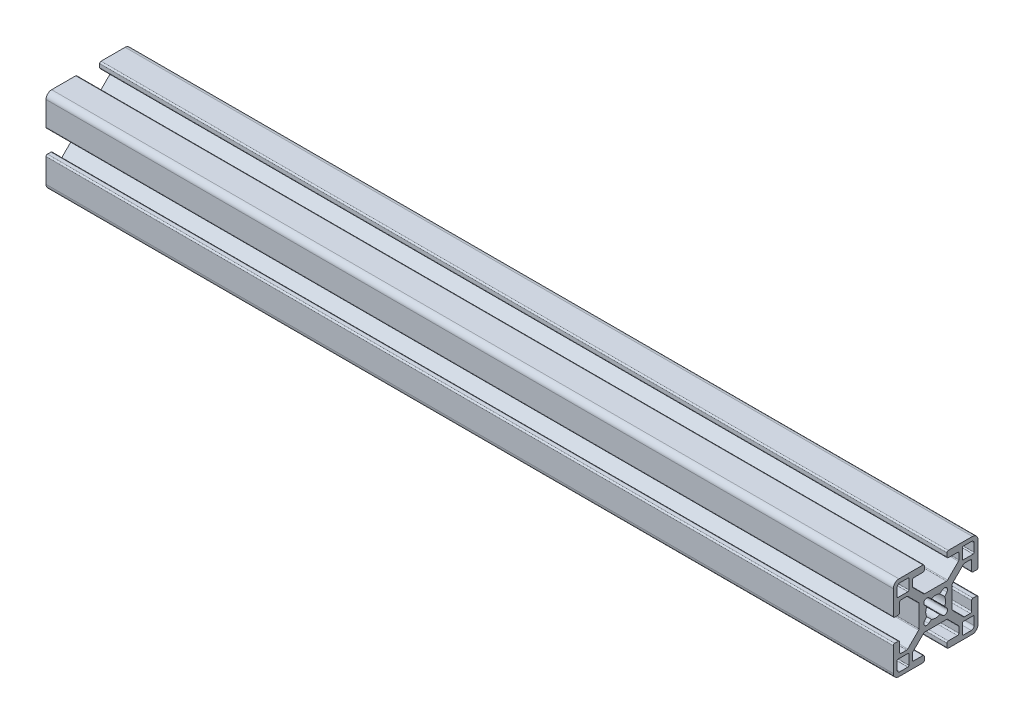
SolidWorks part; units mm, degrees
ref_plane "Front" through (0, 0, 0) normal (0, 0, 1) x (1, 0, 0)
ref_plane "Top" through (0, 0, 0) normal (0, 1, 0) x (1, 0, 0)
ref_plane "Right" through (0, 0, 0) normal (1, 0, 0) x (0, 0, -1)
sketch "Esboço1" plane through (0, 0, 0) normal (0, 1, 0) x (1, 0, 0)
  line L0 (0, 0) -> (300, 0)
  dimension "D1" = 300
other "Perfil com. aluminio PERFIL COMER. 30 X 30(1)"
ref_plane "Plano1" through (0, 0, 0) normal (1, 0, 0) x (0, 0, -1)
sketch "Esboço11" plane through (0, 0, 0) normal (1, 0, 0) x (0, 0, -1)
  line L10 (-3.1849, 1.488) -> (-3.9634, 2.4631)
  line L11 (-2.4631, 3.9634) -> (-1.488, 3.1849)
  line L16 (-9.46, 13.26) -> (-9.46, 9.84)
  line L17 (-9.84, 9.46) -> (-13.26, 9.46)
  line L18 (-13.64, 9.84) -> (-13.64, 12.64)
  line L19 (-12.64, 13.64) -> (-9.84, 13.64)
  line L44 (0, 5.8727) -> (-3.8729, 5.8727)
  line L45 (-4.2264, 6.0192) -> (-8.0736, 9.8663)
  line L46 (-8.22, 10.2198) -> (-8.22, 12.25)
  line L47 (-7.72, 12.75) -> (-4.5, 12.75)
  line L48 (-4, 13.25) -> (-4, 14.5)
  line L49 (-4.5, 15) -> (-13, 15)
  line L50 (-15, 13) -> (-15, 4.5)
  line L51 (-14.5, 4) -> (-13.25, 4)
  line L52 (-12.75, 4.5) -> (-12.75, 7.72)
  line L53 (-12.25, 8.22) -> (-10.2198, 8.22)
  line L54 (-9.8663, 8.0736) -> (-6.0192, 4.2264)
  line L55 (-5.8727, 3.8729) -> (-5.8727, 0)
  line L84 (13.64, 12.64) -> (13.64, 9.84)
  line L91 (15, 4.5) -> (15, 13)
  line L92 (13, 15) -> (4.5, 15)
  line L93 (4, 14.5) -> (4, 13.25)
  line L94 (4.5, 12.75) -> (7.72, 12.75)
  line L95 (8.22, 12.25) -> (8.22, 10.2198)
  line L96 (8.0736, 9.8663) -> (4.2264, 6.0192)
  line L97 (3.8729, 5.8727) -> (0, 5.8727)
  line L98 (1.488, 3.1849) -> (2.4631, 3.9634)
  line L99 (3.9634, 2.4631) -> (3.1849, 1.488)
  line L100 (5.8727, 0) -> (5.8727, 3.8729)
  line L101 (6.0192, 4.2264) -> (9.8663, 8.0736)
  line L102 (10.2198, 8.22) -> (12.25, 8.22)
  line L103 (12.75, 7.72) -> (12.75, 4.5)
  line L104 (13.25, 4) -> (14.5, 4)
  line L105 (13.26, 9.46) -> (9.84, 9.46)
  line L112 (9.46, 9.84) -> (9.46, 13.26)
  line L113 (9.84, 13.64) -> (12.64, 13.64)
  line L114 (12.64, -13.64) -> (9.84, -13.64)
  line L115 (4.5, -15) -> (13, -15)
  line L116 (15, -13) -> (15, -4.5)
  line L117 (14.5, -4) -> (13.25, -4)
  line L118 (12.75, -4.5) -> (12.75, -7.72)
  line L119 (12.25, -8.22) -> (10.2198, -8.22)
  line L120 (9.8663, -8.0736) -> (6.0192, -4.2264)
  line L121 (5.8727, -3.8729) -> (5.8727, 0)
  line L122 (3.1849, -1.488) -> (3.9634, -2.4631)
  line L123 (2.4631, -3.9634) -> (1.488, -3.1849)
  line L124 (0, -5.8727) -> (3.8729, -5.8727)
  line L125 (4.2264, -6.0192) -> (8.0736, -9.8663)
  line L126 (8.22, -10.2198) -> (8.22, -12.25)
  line L133 (7.72, -12.75) -> (4.5, -12.75)
  line L134 (4, -13.25) -> (4, -14.5)
  line L135 (9.46, -13.26) -> (9.46, -9.84)
  line L136 (9.84, -9.46) -> (13.26, -9.46)
  line L137 (13.64, -9.84) -> (13.64, -12.64)
  line L138 (-13.64, -12.64) -> (-13.64, -9.84)
  line L139 (-15, -4.5) -> (-15, -13)
  line L140 (-13, -15) -> (-4.5, -15)
  line L141 (-4, -14.5) -> (-4, -13.25)
  line L142 (-4.5, -12.75) -> (-7.72, -12.75)
  line L143 (-8.22, -12.25) -> (-8.22, -10.2198)
  line L144 (-8.0736, -9.8663) -> (-4.2264, -6.0192)
  line L145 (-3.8729, -5.8727) -> (0, -5.8727)
  line L146 (-1.488, -3.1849) -> (-2.4631, -3.9634)
  line L147 (-3.9634, -2.4631) -> (-3.1849, -1.488)
  line L148 (3.9634, 2.4631) -> (3.1849, 1.488) [skipped]
  line L149 (13.26, 9.46) -> (9.84, 9.46) [skipped]
  line L150 (9.46, 9.84) -> (9.46, 13.26) [skipped]
  line L151 (9.84, 13.64) -> (12.64, 13.64) [skipped]
  line L152 (13.64, 12.64) -> (13.64, 9.84) [skipped]
  line L153 (5.8727, 0) -> (5.8727, 3.8729) [skipped]
  line L154 (6.0192, 4.2264) -> (9.8663, 8.0736) [skipped]
  line L155 (10.2198, 8.22) -> (12.25, 8.22) [skipped]
  line L156 (12.75, 7.72) -> (12.75, 4.5) [skipped]
  line L157 (13.25, 4) -> (14.5, 4) [skipped]
  line L158 (15, 4.5) -> (15, 13) [skipped]
  line L159 (13, 15) -> (4.5, 15) [skipped]
  line L160 (4, 14.5) -> (4, 13.25) [skipped]
  line L161 (4.5, 12.75) -> (7.72, 12.75) [skipped]
  line L162 (8.22, 12.25) -> (8.22, 10.2198) [skipped]
  line L163 (8.0736, 9.8663) -> (4.2264, 6.0192) [skipped]
  line L164 (3.8729, 5.8727) -> (0, 5.8727) [skipped]
  line L165 (3.1849, -1.488) -> (3.9634, -2.4631) [skipped]
  line L166 (9.46, -13.26) -> (9.46, -9.84) [skipped]
  line L167 (9.84, -9.46) -> (13.26, -9.46) [skipped]
  line L168 (13.64, -9.84) -> (13.64, -12.64) [skipped]
  line L169 (12.64, -13.64) -> (9.84, -13.64) [skipped]
  line L170 (0, -5.8727) -> (3.8729, -5.8727) [skipped]
  line L171 (4.2264, -6.0192) -> (8.0736, -9.8663) [skipped]
  line L172 (8.22, -10.2198) -> (8.22, -12.25) [skipped]
  line L173 (7.72, -12.75) -> (4.5, -12.75) [skipped]
  line L174 (4, -13.25) -> (4, -14.5) [skipped]
  line L175 (4.5, -15) -> (13, -15) [skipped]
  line L176 (15, -13) -> (15, -4.5) [skipped]
  line L177 (14.5, -4) -> (13.25, -4) [skipped]
  line L178 (12.75, -4.5) -> (12.75, -7.72) [skipped]
  line L179 (12.25, -8.22) -> (10.2198, -8.22) [skipped]
  line L180 (9.8663, -8.0736) -> (6.0192, -4.2264) [skipped]
  line L181 (5.8727, -3.8729) -> (5.8727, 0) [skipped]
  line L182 (-9.46, -9.84) -> (-9.46, -13.26) [skipped]
  line L183 (-9.84, -13.64) -> (-12.64, -13.64) [skipped]
  line L184 (-13.64, -12.64) -> (-13.64, -9.84) [skipped]
  line L185 (-15, -4.5) -> (-15, -13) [skipped]
  line L186 (-13, -15) -> (-4.5, -15) [skipped]
  line L187 (-4, -14.5) -> (-4, -13.25) [skipped]
  line L188 (-4.5, -12.75) -> (-7.72, -12.75) [skipped]
  line L189 (-8.22, -12.25) -> (-8.22, -10.2198) [skipped]
  line L190 (2.4631, -3.9634) -> (1.488, -3.1849) [skipped]
  line L191 (-1.488, -3.1849) -> (-2.4631, -3.9634) [skipped]
  line L192 (-13.26, -9.46) -> (-9.84, -9.46) [skipped]
  line L193 (-6.0192, -4.2264) -> (-9.8663, -8.0736) [skipped]
  line L194 (-10.2198, -8.22) -> (-12.25, -8.22) [skipped]
  line L195 (-12.75, -7.72) -> (-12.75, -4.5) [skipped]
  line L196 (-13.25, -4) -> (-14.5, -4) [skipped]
  line L197 (-8.0736, -9.8663) -> (-4.2264, -6.0192) [skipped]
  line L198 (-3.8729, -5.8727) -> (0, -5.8727) [skipped]
  line L199 (1.488, 3.1849) -> (2.4631, 3.9634) [skipped]
  line L200 (-3.9634, -2.4631) -> (-3.1849, -1.488) [skipped]
  line L201 (-5.8727, 0) -> (-5.8727, -3.8729) [skipped]
  line L202 (-5.8727, 0) -> (-5.8727, -3.8729)
  line L203 (-6.0192, -4.2264) -> (-9.8663, -8.0736)
  line L204 (-10.2198, -8.22) -> (-12.25, -8.22)
  line L205 (-12.75, -7.72) -> (-12.75, -4.5)
  line L206 (-13.25, -4) -> (-14.5, -4)
  line L207 (-13.26, -9.46) -> (-9.84, -9.46)
  line L208 (-9.46, -9.84) -> (-9.46, -13.26)
  line L209 (-9.84, -13.64) -> (-12.64, -13.64)
  arc A10 (-3.1849, 1.488) -> (-3.5154, 0) centre (0, 0) ccw
  arc A11 (-2.4631, 3.9634) -> (-3.9634, 2.4631) centre (-3.1292, 3.1292) ccw
  arc A12 (0, 3.5154) -> (-1.488, 3.1849) centre (0, 0) ccw
  arc A16 (-9.46, 13.26) -> (-9.84, 13.64) centre (-9.84, 13.26) ccw
  arc A17 (-9.84, 9.46) -> (-9.46, 9.84) centre (-9.84, 9.84) ccw
  arc A18 (-13.64, 9.84) -> (-13.26, 9.46) centre (-13.26, 9.84) ccw
  arc A19 (-12.64, 13.64) -> (-13.64, 12.64) centre (-12.64, 12.64) ccw
  arc A41 (-7.72, 12.75) -> (-8.22, 12.25) centre (-7.72, 12.25) ccw
  arc A42 (-4.5, 12.75) -> (-4, 13.25) centre (-4.5, 13.25) ccw
  arc A43 (-4, 14.5) -> (-4.5, 15) centre (-4.5, 14.5) ccw
  arc A44 (-13, 15) -> (-15, 13) centre (-13, 13) ccw
  arc A45 (-15, 4.5) -> (-14.5, 4) centre (-14.5, 4.5) ccw
  arc A46 (-13.25, 4) -> (-12.75, 4.5) centre (-13.25, 4.5) ccw
  arc A47 (-12.25, 8.22) -> (-12.75, 7.72) centre (-12.25, 7.72) ccw
  arc A50 (-6.0192, 4.2264) -> (-5.8727, 3.8729) centre (-6.3727, 3.8729) cw
  arc A51 (-4.2264, 6.0192) -> (-3.8729, 5.8727) centre (-3.8729, 6.3727) ccw
  arc A52 (-8.22, 10.2198) -> (-8.0736, 9.8663) centre (-7.72, 10.2198) ccw
  arc A53 (-10.2198, 8.22) -> (-9.8663, 8.0736) centre (-10.2198, 7.72) cw
  arc A68 (15, 13) -> (13, 15) centre (13, 13) ccw
  arc A69 (13.64, 12.64) -> (12.64, 13.64) centre (12.64, 12.64) ccw
  arc A70 (4.5, 15) -> (4, 14.5) centre (4.5, 14.5) ccw
  arc A71 (4, 13.25) -> (4.5, 12.75) centre (4.5, 13.25) ccw
  arc A79 (8.22, 12.25) -> (7.72, 12.75) centre (7.72, 12.25) ccw
  arc A80 (8.22, 10.2198) -> (8.0736, 9.8663) centre (7.72, 10.2198) cw
  arc A81 (4.2264, 6.0192) -> (3.8729, 5.8727) centre (3.8729, 6.3727) cw
  arc A82 (1.488, 3.1849) -> (0, 3.5154) centre (0, 0) ccw
  arc A83 (3.9634, 2.4631) -> (2.4631, 3.9634) centre (3.1292, 3.1292) ccw
  arc A84 (3.5154, 0) -> (3.1849, 1.488) centre (0, 0) ccw
  arc A85 (6.0192, 4.2264) -> (5.8727, 3.8729) centre (6.3727, 3.8729) ccw
  arc A86 (10.2198, 8.22) -> (9.8663, 8.0736) centre (10.2198, 7.72) ccw
  arc A87 (12.75, 7.72) -> (12.25, 8.22) centre (12.25, 7.72) ccw
  arc A88 (12.75, 4.5) -> (13.25, 4) centre (13.25, 4.5) ccw
  arc A89 (14.5, 4) -> (15, 4.5) centre (14.5, 4.5) ccw
  arc A97 (13.26, 9.46) -> (13.64, 9.84) centre (13.26, 9.84) ccw
  arc A98 (9.46, 9.84) -> (9.84, 9.46) centre (9.84, 9.84) ccw
  arc A99 (9.84, 13.64) -> (9.46, 13.26) centre (9.84, 13.26) ccw
  arc A100 (13, -15) -> (15, -13) centre (13, -13) ccw
  arc A101 (12.64, -13.64) -> (13.64, -12.64) centre (12.64, -12.64) ccw
  arc A102 (15, -4.5) -> (14.5, -4) centre (14.5, -4.5) ccw
  arc A103 (13.25, -4) -> (12.75, -4.5) centre (13.25, -4.5) ccw
  arc A104 (12.25, -8.22) -> (12.75, -7.72) centre (12.25, -7.72) ccw
  arc A105 (10.2198, -8.22) -> (9.8663, -8.0736) centre (10.2198, -7.72) cw
  arc A106 (6.0192, -4.2264) -> (5.8727, -3.8729) centre (6.3727, -3.8729) cw
  arc A107 (3.1849, -1.488) -> (3.5154, 0) centre (0, 0) ccw
  arc A108 (3.9634, 2.4631) -> (2.4631, 3.9634) centre (3.1292, 3.1292) ccw [skipped]
  arc A109 (13.26, 9.46) -> (13.64, 9.84) centre (13.26, 9.84) ccw [skipped]
  arc A110 (9.46, 9.84) -> (9.84, 9.46) centre (9.84, 9.84) ccw [skipped]
  arc A111 (9.84, 13.64) -> (9.46, 13.26) centre (9.84, 13.26) ccw [skipped]
  arc A112 (13.64, 12.64) -> (12.64, 13.64) centre (12.64, 12.64) ccw [skipped]
  arc A113 (12.75, 7.72) -> (12.25, 8.22) centre (12.25, 7.72) ccw [skipped]
  arc A114 (12.75, 4.5) -> (13.25, 4) centre (13.25, 4.5) ccw [skipped]
  arc A115 (14.5, 4) -> (15, 4.5) centre (14.5, 4.5) ccw [skipped]
  arc A116 (15, 13) -> (13, 15) centre (13, 13) ccw [skipped]
  arc A117 (4.5, 15) -> (4, 14.5) centre (4.5, 14.5) ccw [skipped]
  arc A118 (4, 13.25) -> (4.5, 12.75) centre (4.5, 13.25) ccw [skipped]
  arc A119 (8.22, 12.25) -> (7.72, 12.75) centre (7.72, 12.25) ccw [skipped]
  arc A120 (4.2264, 6.0192) -> (3.8729, 5.8727) centre (3.8729, 6.3727) cw [skipped]
  arc A121 (6.0192, 4.2264) -> (5.8727, 3.8729) centre (6.3727, 3.8729) ccw [skipped]
  arc A122 (10.2198, 8.22) -> (9.8663, 8.0736) centre (10.2198, 7.72) ccw [skipped]
  arc A123 (8.22, 10.2198) -> (8.0736, 9.8663) centre (7.72, 10.2198) cw [skipped]
  arc A124 (2.4631, -3.9634) -> (3.9634, -2.4631) centre (3.1292, -3.1292) ccw [skipped]
  arc A125 (9.46, -13.26) -> (9.84, -13.64) centre (9.84, -13.26) ccw [skipped]
  arc A126 (9.84, -9.46) -> (9.46, -9.84) centre (9.84, -9.84) ccw [skipped]
  arc A127 (13.64, -9.84) -> (13.26, -9.46) centre (13.26, -9.84) ccw [skipped]
  arc A128 (12.64, -13.64) -> (13.64, -12.64) centre (12.64, -12.64) ccw [skipped]
  arc A129 (7.72, -12.75) -> (8.22, -12.25) centre (7.72, -12.25) ccw [skipped]
  arc A130 (4.5, -12.75) -> (4, -13.25) centre (4.5, -13.25) ccw [skipped]
  arc A131 (4, -14.5) -> (4.5, -15) centre (4.5, -14.5) ccw [skipped]
  arc A132 (13, -15) -> (15, -13) centre (13, -13) ccw [skipped]
  arc A133 (15, -4.5) -> (14.5, -4) centre (14.5, -4.5) ccw [skipped]
  arc A134 (13.25, -4) -> (12.75, -4.5) centre (13.25, -4.5) ccw [skipped]
  arc A135 (12.25, -8.22) -> (12.75, -7.72) centre (12.25, -7.72) ccw [skipped]
  arc A136 (6.0192, -4.2264) -> (5.8727, -3.8729) centre (6.3727, -3.8729) cw [skipped]
  arc A137 (4.2264, -6.0192) -> (3.8729, -5.8727) centre (3.8729, -6.3727) ccw [skipped]
  arc A138 (8.22, -10.2198) -> (8.0736, -9.8663) centre (7.72, -10.2198) ccw [skipped]
  arc A139 (10.2198, -8.22) -> (9.8663, -8.0736) centre (10.2198, -7.72) cw [skipped]
  arc A140 (-9.84, -13.64) -> (-9.46, -13.26) centre (-9.84, -13.26) ccw [skipped]
  arc A141 (-13.64, -12.64) -> (-12.64, -13.64) centre (-12.64, -12.64) ccw [skipped]
  arc A142 (-15, -13) -> (-13, -15) centre (-13, -13) ccw [skipped]
  arc A143 (-4.5, -15) -> (-4, -14.5) centre (-4.5, -14.5) ccw [skipped]
  arc A144 (-4, -13.25) -> (-4.5, -12.75) centre (-4.5, -13.25) ccw [skipped]
  arc A145 (-8.22, -12.25) -> (-7.72, -12.75) centre (-7.72, -12.25) ccw [skipped]
  arc A146 (0, -3.5154) -> (1.488, -3.1849) centre (0, 0) ccw [skipped]
  arc A147 (-1.488, -3.1849) -> (0, -3.5154) centre (0, 0) ccw [skipped]
  arc A148 (-3.9634, -2.4631) -> (-2.4631, -3.9634) centre (-3.1292, -3.1292) ccw [skipped]
  arc A149 (-13.26, -9.46) -> (-13.64, -9.84) centre (-13.26, -9.84) ccw [skipped]
  arc A150 (-9.46, -9.84) -> (-9.84, -9.46) centre (-9.84, -9.84) ccw [skipped]
  arc A151 (-12.75, -7.72) -> (-12.25, -8.22) centre (-12.25, -7.72) ccw [skipped]
  arc A152 (-12.75, -4.5) -> (-13.25, -4) centre (-13.25, -4.5) ccw [skipped]
  arc A153 (-14.5, -4) -> (-15, -4.5) centre (-14.5, -4.5) ccw [skipped]
  arc A154 (-4.2264, -6.0192) -> (-3.8729, -5.8727) centre (-3.8729, -6.3727) cw [skipped]
  arc A155 (-6.0192, -4.2264) -> (-5.8727, -3.8729) centre (-6.3727, -3.8729) ccw [skipped]
  arc A156 (-10.2198, -8.22) -> (-9.8663, -8.0736) centre (-10.2198, -7.72) ccw [skipped]
  arc A157 (-8.22, -10.2198) -> (-8.0736, -9.8663) centre (-7.72, -10.2198) cw [skipped]
  arc A158 (3.5154, 0) -> (3.1849, 1.488) centre (0, 0) ccw [skipped]
  arc A159 (3.1849, -1.488) -> (3.5154, 0) centre (0, 0) ccw [skipped]
  arc A160 (1.488, 3.1849) -> (0, 3.5154) centre (0, 0) ccw [skipped]
  arc A161 (-3.5154, 0) -> (-3.1849, -1.488) centre (0, 0) ccw [skipped]
  arc A162 (2.4631, -3.9634) -> (3.9634, -2.4631) centre (3.1292, -3.1292) ccw
  arc A163 (0, -3.5154) -> (1.488, -3.1849) centre (0, 0) ccw
  arc A164 (4.2264, -6.0192) -> (3.8729, -5.8727) centre (3.8729, -6.3727) ccw
  arc A165 (8.22, -10.2198) -> (8.0736, -9.8663) centre (7.72, -10.2198) ccw
  arc A166 (7.72, -12.75) -> (8.22, -12.25) centre (7.72, -12.25) ccw
  arc A167 (4.5, -12.75) -> (4, -13.25) centre (4.5, -13.25) ccw
  arc A168 (4, -14.5) -> (4.5, -15) centre (4.5, -14.5) ccw
  arc A169 (9.46, -13.26) -> (9.84, -13.64) centre (9.84, -13.26) ccw
  arc A170 (9.84, -9.46) -> (9.46, -9.84) centre (9.84, -9.84) ccw
  arc A171 (13.64, -9.84) -> (13.26, -9.46) centre (13.26, -9.84) ccw
  arc A172 (-15, -13) -> (-13, -15) centre (-13, -13) ccw
  arc A173 (-13.64, -12.64) -> (-12.64, -13.64) centre (-12.64, -12.64) ccw
  arc A174 (-4.5, -15) -> (-4, -14.5) centre (-4.5, -14.5) ccw
  arc A175 (-4, -13.25) -> (-4.5, -12.75) centre (-4.5, -13.25) ccw
  arc A176 (-8.22, -12.25) -> (-7.72, -12.75) centre (-7.72, -12.25) ccw
  arc A177 (-8.22, -10.2198) -> (-8.0736, -9.8663) centre (-7.72, -10.2198) cw
  arc A178 (-4.2264, -6.0192) -> (-3.8729, -5.8727) centre (-3.8729, -6.3727) cw
  arc A179 (-1.488, -3.1849) -> (0, -3.5154) centre (0, 0) ccw
  arc A180 (-3.9634, -2.4631) -> (-2.4631, -3.9634) centre (-3.1292, -3.1292) ccw
  arc A181 (-3.5154, 0) -> (-3.1849, -1.488) centre (0, 0) ccw
  arc A182 (-6.0192, -4.2264) -> (-5.8727, -3.8729) centre (-6.3727, -3.8729) ccw
  arc A183 (-10.2198, -8.22) -> (-9.8663, -8.0736) centre (-10.2198, -7.72) ccw
  arc A184 (-12.75, -7.72) -> (-12.25, -8.22) centre (-12.25, -7.72) ccw
  arc A185 (-12.75, -4.5) -> (-13.25, -4) centre (-13.25, -4.5) ccw
  arc A186 (-14.5, -4) -> (-15, -4.5) centre (-14.5, -4.5) ccw
  arc A187 (-13.26, -9.46) -> (-13.64, -9.84) centre (-13.26, -9.84) ccw
  arc A188 (-9.46, -9.84) -> (-9.84, -9.46) centre (-9.84, -9.84) ccw
  arc A189 (-9.84, -13.64) -> (-9.46, -13.26) centre (-9.84, -13.26) ccw
  point P0 (-8.75, 15)
  point P9 (0, 0)
  point P12 (-4.08, 5.8727)
  point P15 (-8.22, 10.0127)
  point P18 (-10.0127, 8.22)
  point P93 (0, 0)
  point P171 (0, 0)
  point P221 (0, 0)
  point P232 (0, 0)
  point P233 (0, 0)
  point P450 (0, 0)
  dimension "D3" = 1.0675
  dimension "D6" = 1.36
  dimension "D9" = 0.38
  dimension "D10" = 1
  dimension "D11" = 2
  dimension "D17" = 135
  dimension "D18" = 1.24
  dimension "D25" = 3.5154
  dimension "D39" = 0.5
  dimension "D20" = 15
  dimension "D26" = 0.5
  dimension "D4" = 167.212
  dimension "D5" = 25.043
  dimension "D7" = 1.36
  dimension "D8" = 4.18
  dimension "D12" = 4.18
  dimension "D13" = 1.24
  dimension "D14" = 2.25
  dimension "D15" = 11
  dimension "D16" = 11
  dimension "D19" = 15
  dimension "D21" = 4.14
  dimension "D22" = 38.606
  dimension "D23" = 25.043
  dimension "D24" = 38.606
  dimension "D27" = 5.8727
  dimension "D28" = 4
  dimension "D29" = 1.2477
  dimension "D30" = 4
  dimension "D33" = 135
  dimension "D38" = 0.5
